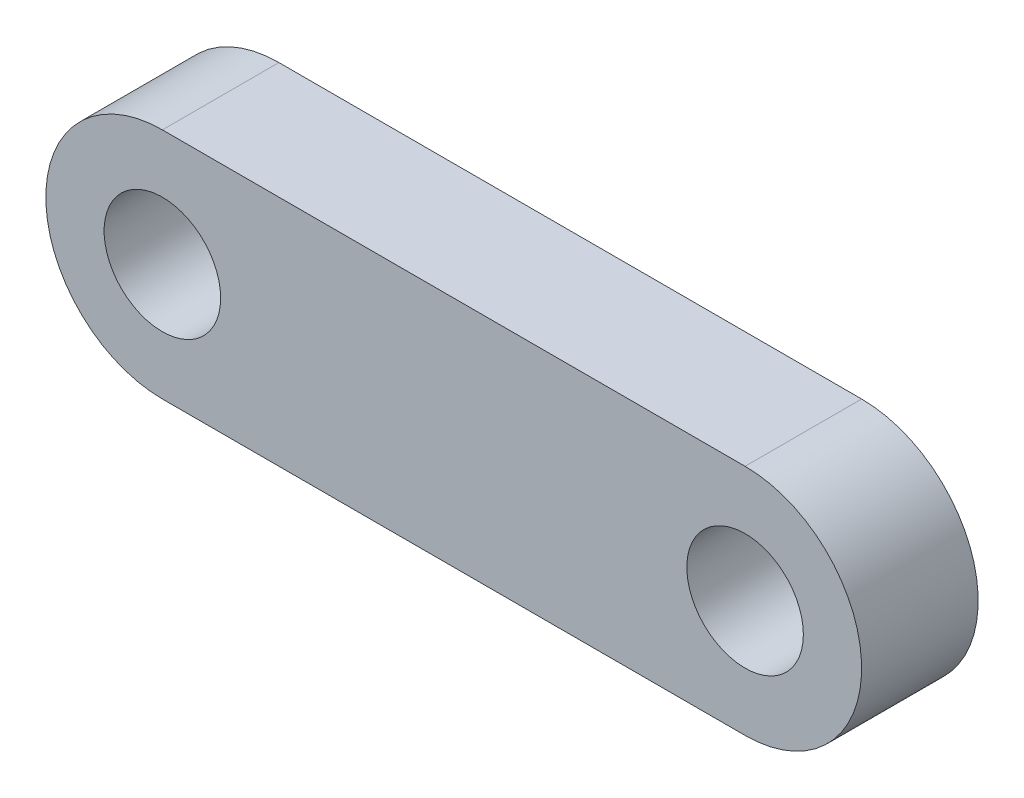
SolidWorks part; units mm, degrees
ref_plane "Front Plane" through (0, 0, 0) normal (0, 0, 1) x (1, 0, 0)
ref_plane "Top Plane" through (0, 0, 0) normal (0, 1, 0) x (1, 0, 0)
ref_plane "Right Plane" through (0, 0, 0) normal (1, 0, 0) x (0, 0, -1)
sketch "Sketch1" plane through (0, 0, 0) normal (0, 0, 1) x (1, 0, 0)
  line L0 (-25, 0) -> (25, 0) construction
  line L1 (-25, 10) -> (25, 10)
  line L2 (-25, -10) -> (25, -10)
  arc A0 (-25, 10) -> (-25, -10) centre (-25, 0) ccw
  arc A1 (25, -10) -> (25, 10) centre (25, 0) ccw
  circle A2 centre (-25, 0) radius 5
  circle A3 centre (25, 0) radius 5
  point P3 (0, 0)
  dimension "D4" = 10
  dimension "D5" = 10
  dimension "D1" = 20
  dimension "D2" = 50
  dimension "D3" = 25
extrude "Boss-Extrude1" add sketch "Sketch1" along normal mid plane 10
